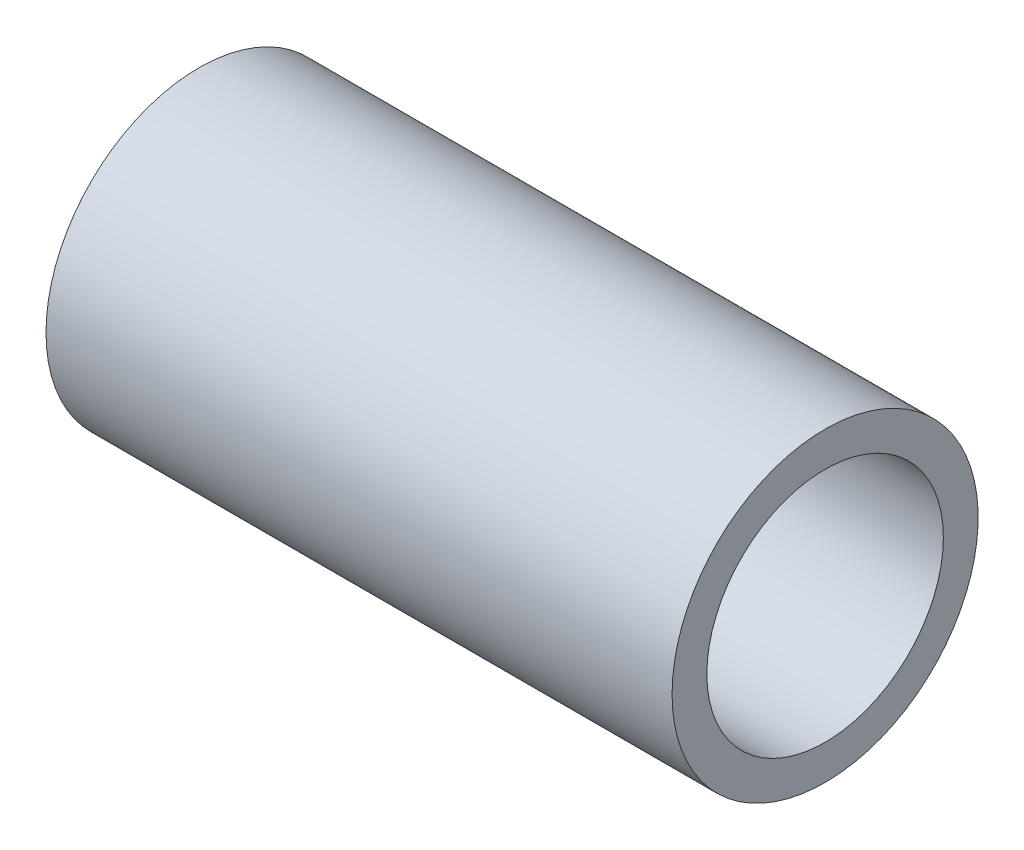
SolidWorks part; units mm, degrees
material "PVC 0.007 Plasticized"
ref_plane "Front Plane" through (0, 0, 0) normal (0, 0, 1) x (1, 0, 0)
ref_plane "Top Plane" through (0, 0, 0) normal (0, 1, 0) x (1, 0, 0)
ref_plane "Right Plane" through (0, 0, 0) normal (1, 0, 0) x (0, 0, -1)
sketch "Sketch1" plane through (0, 0, 0) normal (1, 0, 0) x (0, 0, -1)
  circle A0 centre (0, 0) radius 11
  circle A1 centre (0, 0) radius 8.5
  dimension "D1" = 2.5
extrude "Boss-Extrude1" add sketch "Sketch1" along normal blind 45
